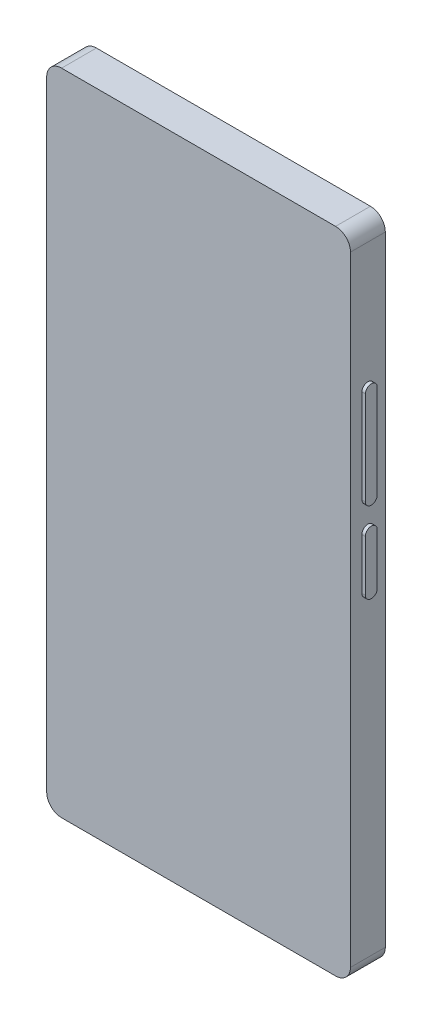
SolidWorks part; units mm, degrees
ref_plane "前视基准面" through (0, 0, 0) normal (0, 0, 1) x (1, 0, 0)
ref_plane "上视基准面" through (0, 0, 0) normal (0, 1, 0) x (1, 0, 0)
ref_plane "右视基准面" through (0, 0, 0) normal (1, 0, 0) x (0, 0, -1)
other "Configuration Table"
sketch "草图1" plane through (0, 0, 0) normal (0, 0, 1) x (1, 0, 0)
  line L1 (-35.75, 76.4) -> (35.75, 76.4)
  line L2 (-35.75, 76.4) -> (-35.75, -76.4)
  line L3 (-35.75, -76.4) -> (35.75, -76.4)
  line L4 (35.75, 76.4) -> (35.75, -76.4)
  line L5 (-35.75, 76.4) -> (35.75, -76.4) construction
  line L6 (-35.75, -76.4) -> (35.75, 76.4) construction
  point P0 (0, 0)
  dimension "D1" = 71.5
  dimension "D2" = 152.8
extrude "凸台-拉伸1" add sketch "草图1" along normal blind 8.2
fillet "圆角3" radius 3.5 1 edges at (-35.75, 76.4, 4.1)
fillet "圆角4" radius 3.5 1 edges at (35.75, 76.4, 4.1)
fillet "圆角5" radius 3.5 1 edges at (35.75, -76.4, 4.1)
fillet "圆角6" radius 3.5 1 edges at (-35.75, -76.4, 4.1)
sketch "草图3" plane through (35.75, 0, 0) normal (1, 0, 0) x (0, 0, -1)
  line L2 (-5.5, 43.0565) -> (-5.5, 21.0565)
  line L4 (-2.7035, 42.9159) -> (-2.7035, 20.9713)
  line L5 (-5.5, 43.0565) -> (-2.7035, 20.9713) construction
  line L6 (-5.5, 21.0565) -> (-2.7035, 42.9159) construction
  arc A0 (-2.7035, 42.9159) -> (-5.5, 43.0565) centre (-4.1, 43.0213) ccw
  arc A1 (-2.7035, 20.9713) -> (-5.5, 21.0565) centre (-4.1, 21.0717) cw
  point P0 (-4.1, 32)
  dimension "D1" = 22
  dimension "D2" = 2.8
extrude "凸台-拉伸3" add sketch "草图3" along normal blind 0.8
sketch "草图4" plane through (35.75, 0, 0) normal (1, 0, 0) x (0, 0, -1)
  line L8 (-5.5, 14) -> (-5.5, 2)
  line L10 (-2.7, 14) -> (-2.7, 2)
  line L11 (-5.5, 14) -> (-2.7, 2) construction
  line L12 (-5.5, 2) -> (-2.7, 14) construction
  arc A0 (-2.7, 14) -> (-5.5, 14) centre (-4.1, 14) ccw
  arc A1 (-2.7, 2) -> (-5.5, 2) centre (-4.1, 2) cw
  point P0 (-4.1, 8)
  point P5 (-4.1, 8)
  dimension "D1" = 12
  dimension "D2" = 2.8
extrude "凸台-拉伸4" add sketch "草图4" along normal blind 0.8
sketch "草图5" plane through (0, 0, 0) normal (0, 0, -1) x (-1, 0, 0)
  line L1 (-33, 73) -> (9, 73)
  line L2 (-33, 73) -> (-33, 31)
  line L3 (-33, 31) -> (9, 31)
  line L4 (9, 73) -> (9, 31)
  line L5 (-33, 73) -> (9, 31) construction
  line L6 (-33, 31) -> (9, 73) construction
  point P0 (-12, 52)
  dimension "D1" = 42
  dimension "D2" = 42
extrude "凸台-拉伸5" add sketch "草图5" along normal blind 1.5
fillet "圆角10" radius 3.5 1 edges at (33, 73, -0.75)
fillet "圆角11" radius 3.5 1 edges at (-9, 73, -0.75)
fillet "圆角12" radius 3.5 1 edges at (33, 31, -0.75)
fillet "圆角13" radius 3.5 1 edges at (-9, 31, -0.75)
sketch "草图6" plane through (0, -76.4, 0) normal (0, -1, 0) x (-1, 0, 0)
  line L1 (3, -6.35) -> (-3, -6.35)
  line L2 (4.5, -4.85) -> (4.5, -3.35)
  line L3 (3, -1.85) -> (-3, -1.85)
  line L4 (-4.5, -4.85) -> (-4.5, -3.35)
  line L5 (4.5, -6.35) -> (-4.5, -1.85) construction
  line L6 (4.5, -1.85) -> (-4.5, -6.35) construction
  arc A0 (-3, -6.35) -> (-4.5, -4.85) centre (-3, -4.85) cw
  arc A1 (4.5, -3.35) -> (3, -1.85) centre (3, -3.35) ccw
  arc A2 (3, -6.35) -> (4.5, -4.85) centre (3, -4.85) ccw
  arc A3 (-3, -1.85) -> (-4.5, -3.35) centre (-3, -3.35) ccw
  point P0 (0, -4.1)
  dimension "D2" = 1.5
  dimension "D1" = 9
  dimension "D3" = 4.5
extrude "切除-拉伸1" cut sketch "草图6" against normal blind 10
sketch "草图7" plane through (0, -66.4, 0) normal (0, -1, 0) x (-1, 0, 0)
  line L1 (3, -4.35) -> (-3, -4.35)
  line L2 (3, -4.35) -> (3, -3.85)
  line L3 (3, -3.85) -> (-3, -3.85)
  line L4 (-3, -4.35) -> (-3, -3.85)
  line L5 (3, -4.35) -> (-3, -3.85) construction
  line L6 (3, -3.85) -> (-3, -4.35) construction
  point P0 (0, -4.1)
  dimension "D1" = 6
  dimension "D2" = 0.5
extrude "凸台-拉伸6" add sketch "草图7" along normal blind 8
sketch "草图8" plane through (0, -76.4, 0) normal (0, -1, 0) x (-1, 0, 0)
  line L0 (0, -8.2) -> (0, 0)
  line L1 (32.25, -8.2) -> (-32.25, -8.2) construction
  line L2 (-8, -8.2) -> (-8, 0)
  line L3 (32.25, 0) -> (-32.25, 0) construction
  line L4 (8, -8.2) -> (8, 0)
  line L6 (9.9163, -3.5393) -> (10.3163, -3.5393)
  line L7 (9.6163, -3.8393) -> (9.6163, -5.2393)
  line L8 (9.9163, -5.5393) -> (10.3163, -5.5393)
  line L9 (10.6163, -3.8393) -> (10.6163, -5.2393)
  line L10 (9.6163, -3.5393) -> (10.6163, -5.5393) construction
  line L11 (9.6163, -5.5393) -> (10.6163, -3.5393) construction
  circle A0 centre (-9.9423, -4.1) radius 1.25
  circle A1 centre (-12.9423, -4.1) radius 1.25
  circle A2 centre (-15.9423, -4.1) radius 1.25
  circle A3 centre (-18.9423, -4.1) radius 1.25
  circle A4 centre (-21.9423, -4.1) radius 1.25
  circle A5 centre (-24.9423, -4.1) radius 1.25
  circle A6 centre (-27.9423, -4.1) radius 1.25
  arc A7 (9.9163, -3.5393) -> (9.6163, -3.8393) centre (9.9163, -3.8393) ccw
  arc A8 (9.6163, -5.2393) -> (9.9163, -5.5393) centre (9.9163, -5.2393) ccw
  arc A9 (10.6163, -5.2393) -> (10.3163, -5.5393) centre (10.3163, -5.2393) cw
  arc A10 (10.6163, -3.8393) -> (10.3163, -3.5393) centre (10.3163, -3.8393) ccw
  point P14 (10.1163, -4.5393)
  dimension "D3" = 2.5
  dimension "D7" = 0.3
  dimension "D8" = 0.3
  dimension "D1" = 8
  dimension "D5" = 1
  dimension "D6" = 2
  dimension "D2" = 8
  dimension "D4" = 7
extrude "切除-拉伸2" cut sketch "草图8" against normal blind 10 contours A0 | A1 | A2 | A3 | A4 | A5 | A6
sketch "草图11" plane through (0, -76.4, 0) normal (0, -1, 0) x (1, 0, 0)
  line L1 (-9.2, 5.1) -> (-8.8, 5.1)
  line L2 (-9.5, 4.8) -> (-9.5, 3.4)
  line L3 (-9.2, 3.1) -> (-8.8, 3.1)
  line L4 (-8.5, 4.8) -> (-8.5, 3.4)
  line L5 (-9.5, 5.1) -> (-8.5, 3.1) construction
  line L6 (-9.5, 3.1) -> (-8.5, 5.1) construction
  arc A0 (-9.2, 3.1) -> (-9.5, 3.4) centre (-9.2, 3.4) cw
  arc A1 (-8.8, 3.1) -> (-8.5, 3.4) centre (-8.8, 3.4) ccw
  arc A2 (-8.8, 5.1) -> (-8.5, 4.8) centre (-8.8, 4.8) cw
  arc A3 (-9.5, 4.8) -> (-9.2, 5.1) centre (-9.2, 4.8) cw
  point P0 (-9, 4.1)
  dimension "D3" = 0.3
  dimension "D1" = 1
  dimension "D2" = 2
extrude "切除-拉伸3" cut sketch "草图11" against normal blind 10
sketch "草图13" plane through (0, 0, -1.5) normal (0, 0, -1) x (-1, 0, 0)
  line L1 (-29.5, 69.5) -> (5.5, 69.5)
  line L2 (-29.5, 69.5) -> (-29.5, 34.5)
  line L3 (-29.5, 34.5) -> (5.5, 34.5)
  line L4 (5.5, 69.5) -> (5.5, 34.5)
  line L5 (-29.5, 69.5) -> (5.5, 34.5) construction
  line L6 (-29.5, 34.5) -> (5.5, 69.5) construction
  point P0 (-12, 52)
  dimension "D1" = 35
  dimension "D2" = 35
extrude "凸台-拉伸7" add sketch "草图13" along normal blind 1.5
fillet "圆角14" radius 3.5 4 edges at (-5.5, 34.5, -2.25) (29.5, 34.5, -2.25) (-5.5, 69.5, -2.25) (29.5, 69.5, -2.25)
sketch "草图14" plane through (0, -76.4, 0) normal (0, -1, 0) x (-1, 0, 0)
  line L0 (16, -4.0502) -> (28, -4.1498) construction
  line L1 (16.0124, -2.5503) -> (28.0124, -2.6498)
  line L2 (15.9876, -5.5502) -> (27.9876, -5.6497)
  arc A0 (16.0124, -2.5503) -> (15.9876, -5.5502) centre (16, -4.0502) ccw
  arc A1 (27.9876, -5.6497) -> (28.0124, -2.6498) centre (28, -4.1498) ccw
  point P2 (22, -4.1)
  dimension "D2" = 1.5
  dimension "D1" = 12
extrude "切除-拉伸4" cut sketch "草图14" against normal blind 10
